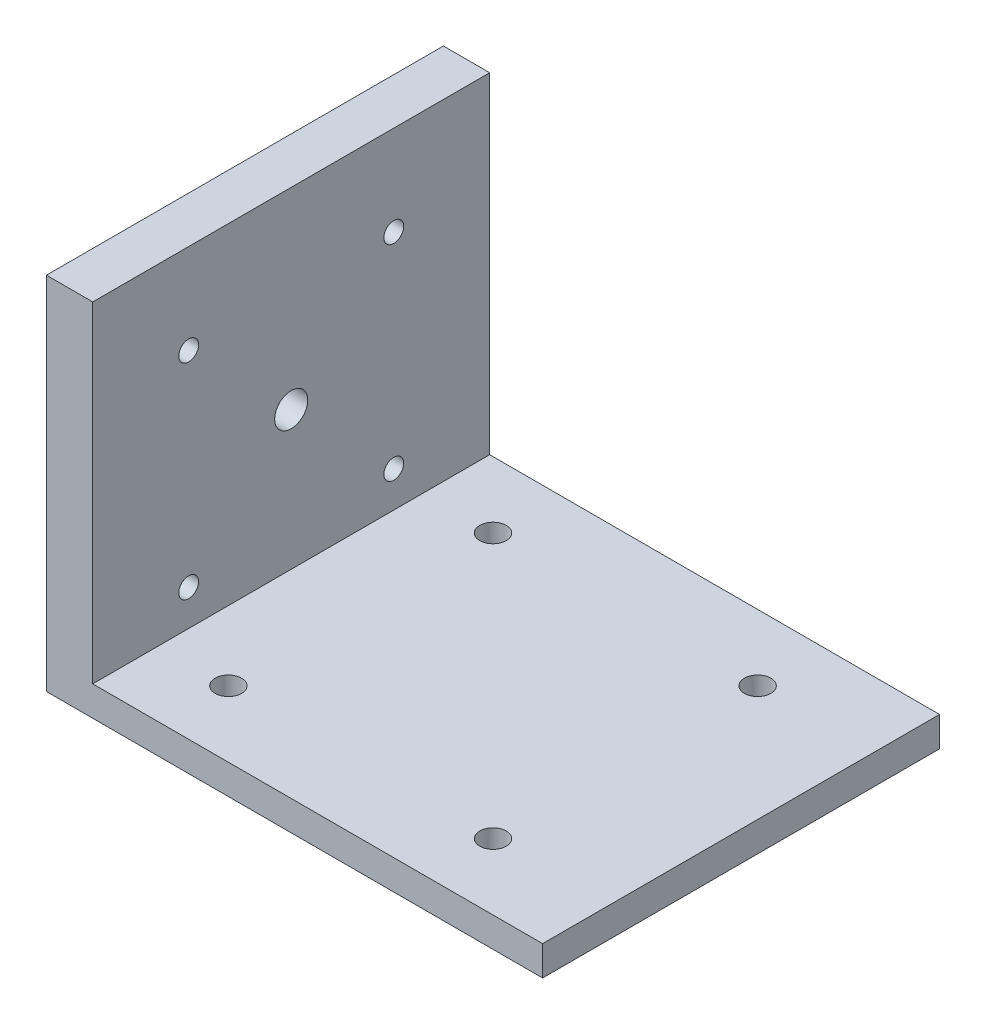
SolidWorks part; units mm, degrees
ref_plane "Front Plane" through (0, 0, 0) normal (0, 0, 1) x (1, 0, 0)
ref_plane "Top Plane" through (0, 0, 0) normal (0, 1, 0) x (1, 0, 0)
ref_plane "Right Plane" through (0, 0, 0) normal (1, 0, 0) x (0, 0, -1)
sketch "Sketch1" plane through (0, 0, 0) normal (0, 1, 0) x (1, 0, 0)
  line L1 (-37.5, 30) -> (37.5, 30)
  line L2 (-37.5, 30) -> (-37.5, -30)
  line L3 (-37.5, -30) -> (37.5, -30)
  line L4 (37.5, 30) -> (37.5, -30)
  line L5 (0, -30) -> (0, 30) construction
  line L6 (-37.5, 0) -> (37.5, 0) construction
  point P0 (0, 0)
  dimension "D1" = 60
  dimension "D2" = 75
extrude "Boss-Extrude1" add sketch "Sketch1" along normal blind 4.5
sketch "Sketch2" plane through (0, 4.5, 0) normal (0, 1, 0) x (1, 0, 0)
  line L0 (0, 0) -> (-47.9452, 0) construction
  line L1 (37.5, 30) -> (-37.5, 30) construction
  line L2 (-37.5, 30) -> (-30.5, 30)
  line L3 (-37.5, 30) -> (-37.5, -30)
  line L4 (-37.5, -30) -> (-30.5, -30)
  line L5 (-30.5, 30) -> (-30.5, -30)
  line L6 (-34, -30) -> (-34, 30) construction
  line L7 (-37.5, 0) -> (-30.5, 0) construction
  line L8 (-37.5, 30) -> (-37.5, -30) construction
  point P3 (-34, 0)
  dimension "D1" = 0
  dimension "D2" = 0
  dimension "D3" = 7
extrude "Boss-Extrude2" add sketch "Sketch2" along normal blind 50
sketch "Sketch3" plane through (-37.5, 0, 0) normal (-1, 0, 0) x (0, 0, 1)
  line L0 (0, 0) -> (0, 55.9415) construction
  line L1 (0, 4.5) -> (41.2695, 4.5) construction
  line L2 (-30, 0) -> (30, 0) construction
  line L3 (0, 25.4) -> (-19.4355, 44.8355) construction
  line L4 (-15.9, 46.3) -> (15.9, 46.3) construction
  line L5 (-20.9, 41.3) -> (-20.9, 9.5) construction
  line L6 (-15.9, 4.5) -> (15.9, 4.5) construction
  line L7 (20.9, 41.3) -> (20.9, 9.5) construction
  line L8 (0, 4.5) -> (0, 46.3) construction
  line L9 (-20.9, 25.4) -> (20.9, 25.4) construction
  arc A0 (-15.9, 4.5) -> (-20.9, 9.5) centre (-15.9, 9.5) cw construction
  arc A1 (15.9, 4.5) -> (20.9, 9.5) centre (15.9, 9.5) ccw construction
  arc A2 (20.9, 41.3) -> (15.9, 46.3) centre (15.9, 41.3) ccw construction
  arc A3 (-20.9, 41.3) -> (-15.9, 46.3) centre (-15.9, 41.3) cw construction
  circle A4 centre (-15.5, 40.9) radius 1.5
  circle A5 centre (15.5, 40.9) radius 1.5
  circle A6 centre (15.5, 9.9) radius 1.5
  circle A7 centre (-15.5, 9.9) radius 1.5
  circle A8 centre (0, 25.4) radius 2.5
  point P7 (0, 25.4)
  point P17 (20.9, 46.3)
  point P21 (-20.9, 46.3)
  dimension "D4" = 5
  dimension "D5" = 3
  dimension "D7" = 5
  dimension "D1" = 4.5
  dimension "D2" = 41.8
  dimension "D3" = 0
  dimension "D6" = 15.5
extrude "Cut-Extrude1" cut sketch "Sketch3" against normal blind 10
sketch "Sketch6" plane through (0, 4.5, 0) normal (0, 1, 0) x (1, 0, 0)
  line L0 (-30.5, -30) -> (-30.5, 30) construction
  line L1 (25.5, 25.5) -> (-25.5, 25.5) construction
  line L2 (25.5, 25.5) -> (25.5, -25.5) construction
  line L3 (25.5, -25.5) -> (-25.5, -25.5) construction
  line L4 (-25.5, 25.5) -> (-25.5, -25.5) construction
  line L5 (0, -25.5) -> (0, 25.5) construction
  line L6 (25.5, 0) -> (-25.5, 0) construction
  line L7 (0, 0) -> (25.5, 25.5) construction
  circle A0 centre (20, 20) radius 2
  circle A1 centre (-20, 20) radius 2
  circle A2 centre (20, -20) radius 2
  circle A3 centre (-20, -20) radius 2
  point P0 (0, 0)
  dimension "D2" = 4
  dimension "D1" = 5
  dimension "D3" = 20
  dimension "D4" = 51
  dimension "D5" = 51
extrude "Cut-Extrude2" cut sketch "Sketch6" against normal blind 10
